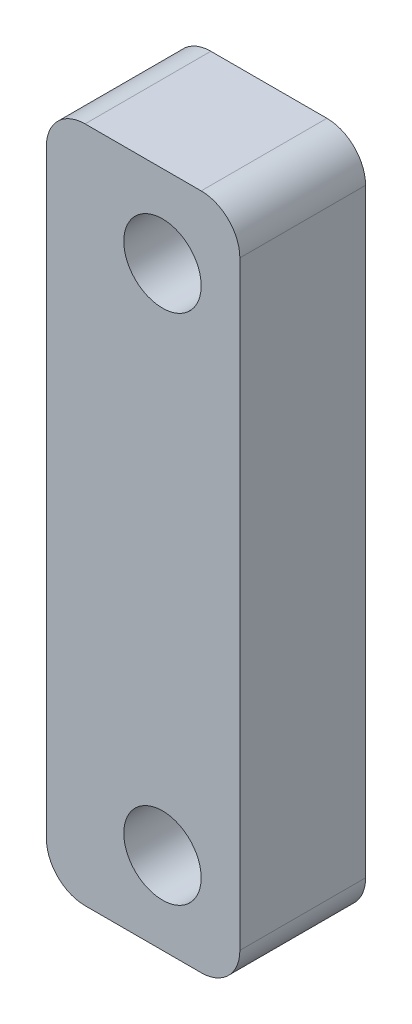
SolidWorks part; units mm, degrees
material "ABS"
ref_plane "Plano frontal" through (0, 0, 0) normal (0, 0, 1) x (1, 0, 0)
ref_plane "Plano superior" through (0, 0, 0) normal (0, 1, 0) x (1, 0, 0)
ref_plane "Plano direito" through (0, 0, 0) normal (1, 0, 0) x (0, 0, -1)
sketch "Esboço2" plane through (0, 0, 0) normal (0, 0, 1) x (1, 0, 0)
  line L0 (0, 2) -> (0, 33)
  line L1 (2, 35) -> (8, 35)
  line L2 (10, 33) -> (10, 2)
  line L3 (2, 0) -> (8, 0)
  arc A0 (0, 2) -> (2, 0) centre (2, 2) ccw
  arc A1 (8, 35) -> (10, 33) centre (8, 33) cw
  arc A2 (0, 33) -> (2, 35) centre (2, 33) cw
  arc A3 (10, 2) -> (8, 0) centre (8, 2) cw
  circle A4 centre (6, 4.25) radius 2
  circle A5 centre (6, 30.75) radius 2
  point P7 (0, 0)
  dimension "D1" = 2
  dimension "D2" = 2
  dimension "D3" = 2
  dimension "D4" = 2
  dimension "D5" = 4
  dimension "D7" = 26.5
  dimension "D6" = 4.25
  dimension "D8" = 4
extrude "Ressalto-extrusão1" add sketch "Esboço2" along normal blind 4.5
sketch "Esboço3" plane through (0, 0, 0) normal (0, 0, -1) x (-1, 0, 0)
  line L4 (0, 2) -> (0, 33)
  line L5 (-2, 35) -> (-8, 35)
  line L6 (-10, 33) -> (-10, 2)
  line L7 (-8, 0) -> (-2, 0)
  line L8 (0, 2) -> (0, 33)
  line L9 (-2, 35) -> (-8, 35)
  line L10 (-10, 33) -> (-10, 2)
  line L11 (-8, 0) -> (-2, 0)
  circle A0 centre (-6, 30.75) radius 2 construction
  circle A1 centre (-6, 4.25) radius 2 construction
  circle A2 centre (-6, 30.75) radius 2
  circle A3 centre (-6, 4.25) radius 2
  arc A4 (-2, 0) -> (0, 2) centre (-2, 2) ccw
  arc A5 (0, 33) -> (-2, 35) centre (-2, 33) ccw
  arc A6 (-8, 35) -> (-10, 33) centre (-8, 33) ccw
  arc A7 (-10, 2) -> (-8, 0) centre (-8, 2) ccw
  arc A8 (-2, 0) -> (0, 2) centre (-2, 2) ccw
  arc A9 (0, 33) -> (-2, 35) centre (-2, 33) ccw
  arc A10 (-8, 35) -> (-10, 33) centre (-8, 33) ccw
  arc A11 (-10, 2) -> (-8, 0) centre (-8, 2) ccw
  dimension "D1" = 0
extrude "Ressalto-extrusão2" add sketch "Esboço3" along normal blind 2 contours A8 L8 A9 L9 A10 L10 A11 L11
sketch "Esboço4" plane through (0, 0, 4.5) normal (0, 0, 1) x (1, 0, 0)
  circle A0 centre (6, 4.25) radius 2 construction
  circle A1 centre (6, 30.75) radius 2 construction
  circle A2 centre (6, 4.25) radius 2
  circle A3 centre (6, 30.75) radius 2
extrude "Corte-extrusão2" cut sketch "Esboço4" against normal through all
